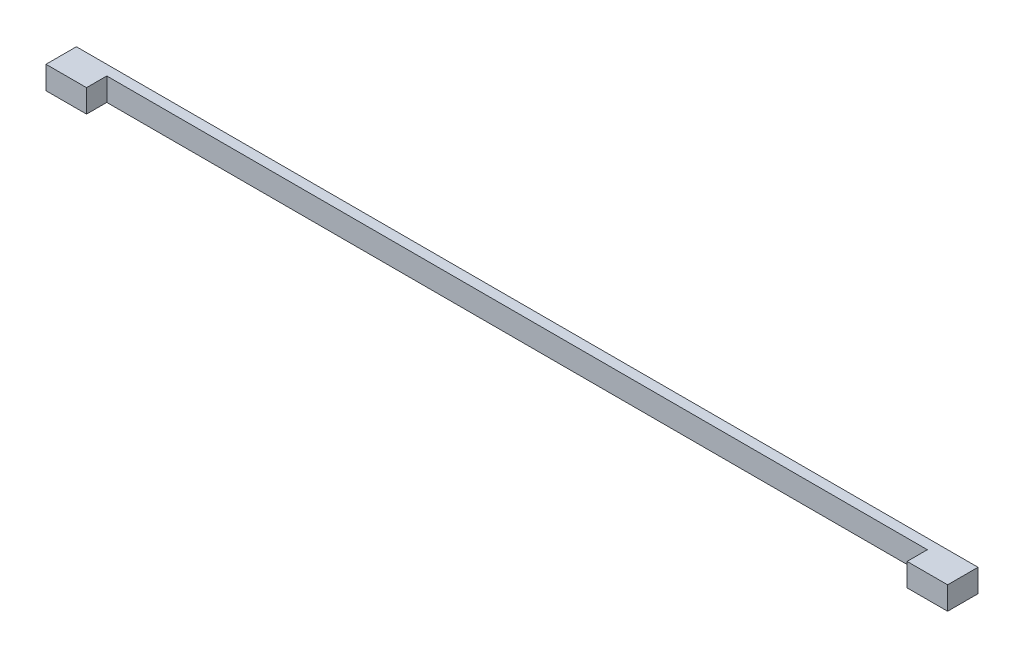
SolidWorks part; units mm, degrees
ref_plane "정면" through (0, 0, 0) normal (0, 0, 1) x (1, 0, 0)
ref_plane "윗면" through (0, 0, 0) normal (0, 1, 0) x (1, 0, 0)
ref_plane "우측면" through (0, 0, 0) normal (1, 0, 0) x (0, 0, -1)
sketch "스케치1" plane through (0, 0, 0) normal (0, 0, 1) x (1, 0, 0)
  line L1 (-222.5, 5.6601) -> (222.5, 5.6601)
  line L2 (-222.5, 5.6601) -> (-222.5, -5.6601)
  line L3 (-222.5, -5.6601) -> (222.5, -5.6601)
  line L4 (222.5, 5.6601) -> (222.5, -5.6601)
  line L5 (-222.5, 5.6601) -> (222.5, -5.6601) construction
  line L6 (-222.5, -5.6601) -> (222.5, 5.6601) construction
  point P0 (0, 0)
  dimension "D1" = 445
extrude "보스-돌출1" add sketch "스케치1" along normal blind 5
sketch "스케치2" plane through (0, 0, 5) normal (0, 0, 1) x (1, 0, 0)
  line L0 (222.5, 5.6601) -> (-222.5, 5.6601) construction
  line L1 (-222.5, -5.6601) -> (-202.5, -5.6601)
  line L2 (-222.5, -5.6601) -> (-222.5, 5.6601)
  line L3 (-222.5, 5.6601) -> (-202.5, 5.6601)
  line L4 (-202.5, -5.6601) -> (-202.5, 5.6601)
  line L5 (-222.5, -5.6601) -> (222.5, -5.6601) construction
  line L6 (222.5, 5.6601) -> (202.5, 5.6601)
  line L7 (222.5, 5.6601) -> (222.5, -5.6601)
  line L8 (222.5, -5.6601) -> (202.5, -5.6601)
  line L9 (202.5, 5.6601) -> (202.5, -5.6601)
  dimension "D1" = 20
  dimension "D2" = 20
extrude "보스-돌출2" add sketch "스케치2" along normal blind 10
